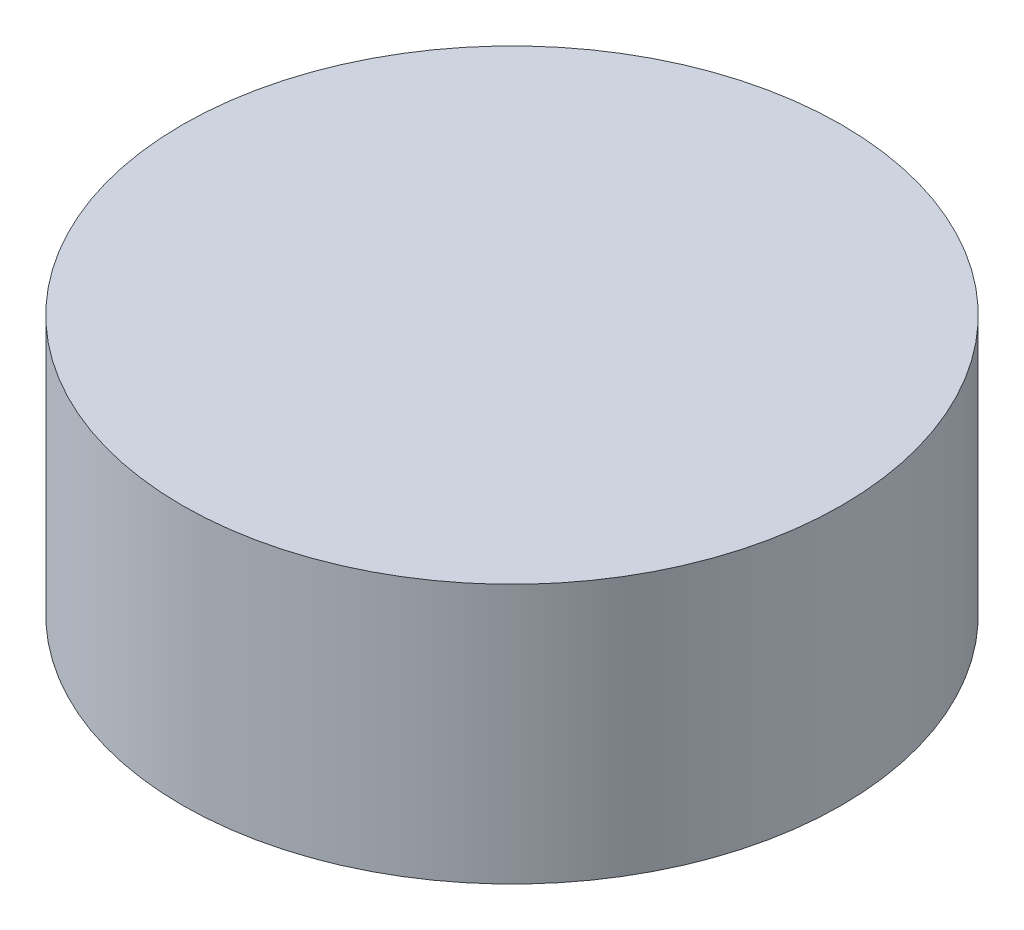
SolidWorks part; units mm, degrees
ref_plane "Front Plane" through (0, 0, 0) normal (0, 0, 1) x (1, 0, 0)
ref_plane "Top Plane" through (0, 0, 0) normal (0, 1, 0) x (1, 0, 0)
ref_plane "Right Plane" through (0, 0, 0) normal (1, 0, 0) x (0, 0, -1)
sketch "Sketch1" plane through (0, 0, 0) normal (0, 1, 0) x (1, 0, 0)
  circle A0 centre (0, 0) radius 6.35
  dimension "D1" = 12.7
extrude "Boss-Extrude1" add sketch "Sketch1" along normal blind 5
